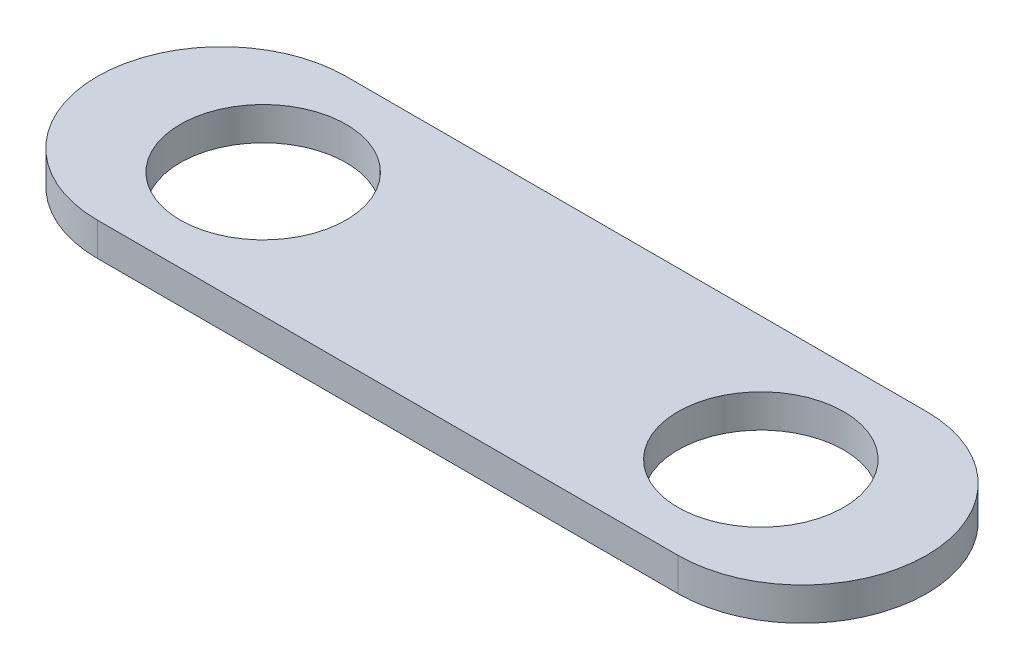
SolidWorks part; units mm, degrees
ref_plane "Front Plane" through (0, 0, 0) normal (0, 0, 1) x (1, 0, 0)
ref_plane "Top Plane" through (0, 0, 0) normal (0, 1, 0) x (1, 0, 0)
ref_plane "Right Plane" through (0, 0, 0) normal (1, 0, 0) x (0, 0, -1)
sketch "Sketch1" plane through (0, 0, 0) normal (0, 1, 0) x (1, 0, 0)
  line L1 (0, 0) -> (50, 0)
  line L2 (0, 0) -> (0, 15)
  line L3 (0, 15) -> (50, 15)
  line L4 (50, 0) -> (50, 15)
  dimension "D1" = 50
  dimension "D2" = 15
extrude "Boss-Extrude1" add sketch "Sketch1" along normal blind 2
sketch "Sketch2" plane through (0, 2, 0) normal (0, 1, 0) x (1, 0, 0)
  line L0 (25, 15) -> (25, 0) construction
  line L1 (50, 15) -> (0, 15) construction
  line L2 (0, 0) -> (50, 0) construction
  circle A0 centre (10, 7.5) radius 5
  circle A1 centre (40, 7.5) radius 5
extrude "Cut-Extrude1" cut sketch "Sketch2" against normal blind 2
sketch "Sketch5" plane through (0, 2, 0) normal (0, 1, 0) x (1, 0, 0)
  line L0 (25, 15) -> (25, 0) construction
  line L1 (50, 15) -> (0, 15) construction
  line L2 (0, 0) -> (50, 0) construction
  line L3 (7.5, 15) -> (0, 15)
  line L4 (0, 15) -> (0, 7.5)
  line L5 (0, 7.5) -> (0, 0)
  line L6 (0, 0) -> (7.5, 0)
  line L7 (50, 0) -> (42.5, 0)
  line L8 (50, 7.5) -> (50, 0)
  line L9 (50, 15) -> (50, 7.5)
  line L10 (42.5, 15) -> (50, 15)
  circle A0 centre (7.5, 7.5) radius 7.5
  circle A1 centre (42.5, 7.5) radius 7.5
  circle A2 centre (42.5, 7.5) radius 7.5
  point P10 (7.5, 15)
  line M5 (0, 15) -> (0, 0)
  line M6 (0, 0) -> (50, 0)
  line M7 (50, 0) -> (50, 15)
  line M8 (50, 15) -> (0, 15)
extrude "Cut-Extrude2" cut sketch "Sketch5" against normal blind 2 contours A0 M8 M5 | A0 M5 M6 | A1 M8 M7 | A1 M7 M6
